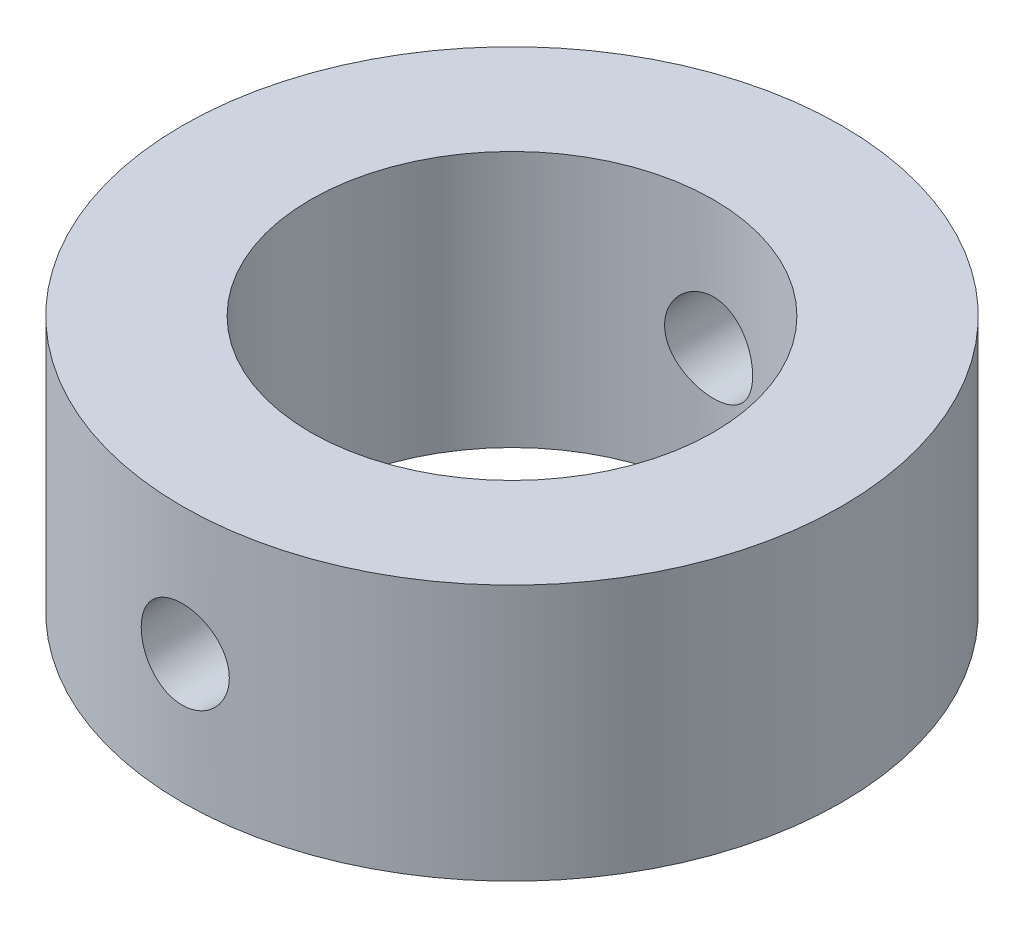
SolidWorks part; units mm, degrees
ref_plane "Front Plane" through (0, 0, 0) normal (0, 0, 1) x (1, 0, 0)
ref_plane "Top Plane" through (0, 0, 0) normal (0, 1, 0) x (1, 0, 0)
ref_plane "Right Plane" through (0, 0, 0) normal (1, 0, 0) x (0, 0, -1)
sketch "Sketch1" plane through (0, 0, 0) normal (0, 1, 0) x (1, 0, 0)
  circle A0 centre (0, 0) radius 18
  circle A1 centre (0, 0) radius 11
  dimension "D1" = 36
  dimension "D2" = 22
extrude "Boss-Extrude1" add sketch "Sketch1" along normal blind 14
sketch "Sketch3" plane through (0, 0, 0) normal (0, 0, 1) x (1, 0, 0)
  line L0 (0, 20.7972) -> (0, -8.0275) construction
  circle A0 centre (0, 7) radius 2.4042
  dimension "D1" = 7
extrude "Cut-Extrude1" cut sketch "Sketch3" against normal through all both and the other way through all
